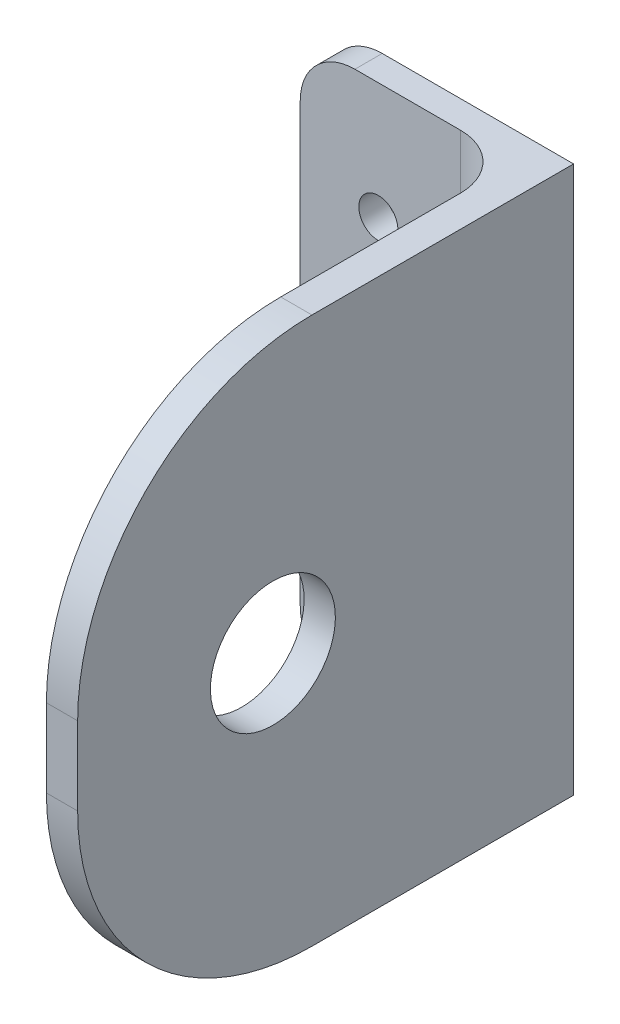
SolidWorks part; units mm, degrees
ref_plane "Plan de face" through (0, 0, 0) normal (0, 0, 1) x (1, 0, 0)
ref_plane "Plan de dessus" through (0, 0, 0) normal (0, 1, 0) x (1, 0, 0)
ref_plane "Plan de droite" through (0, 0, 0) normal (1, 0, 0) x (0, 0, -1)
sketch "Esquisse1" plane through (0, 0, 0) normal (0, 0, 1) x (1, 0, 0)
  line L0 (9.2703, 7.7568) -> (16.2703, 7.7568)
  line L1 (3.2703, 7.7568) -> (9.2703, 7.7568)
  line L2 (-3.7297, 0.7568) -> (-3.7297, -55.2432)
  line L3 (3.2703, -62.2432) -> (9.2703, -62.2432)
  line L4 (16.2703, 0.7568) -> (16.2703, -55.2432)
  line L5 (16.2703, 7.7568) -> (16.2703, 0.7568)
  line L6 (16.2703, -55.2432) -> (16.2703, -62.2432)
  line L7 (16.2703, -62.2432) -> (9.2703, -62.2432)
  arc A0 (-3.7297, -55.2432) -> (3.2703, -62.2432) centre (3.2703, -55.2432) ccw
  arc A3 (3.2703, 7.7568) -> (-3.7297, 0.7568) centre (3.2703, 0.7568) ccw
  point P8 (16.2703, -62.2432)
  point P11 (16.2703, 7.7568)
  point P14 (-3.7297, 7.7568)
  dimension "D3" = 7
  dimension "D1" = 20
  dimension "D2" = 70
extrude "Boss.-Extru.1" add sketch "Esquisse1" along normal blind 3.5
sketch "Esquisse2" plane through (0, 0, 3.5) normal (0, 0, 1) x (1, 0, 0)
  line L0 (16.2703, -62.2432) -> (16.2703, 7.7568) construction
  line L1 (16.2703, 7.7568) -> (3.2703, 7.7568) construction
  line L2 (3.2703, -62.2432) -> (16.2703, -62.2432) construction
  circle A0 centre (6.2703, -7.2432) radius 2.5
  circle A1 centre (6.2703, -47.2432) radius 2.5
  dimension "D1" = 10
  dimension "D2" = 10
  dimension "D3" = 5
  dimension "D4" = 5
  dimension "D5" = 15
  dimension "D6" = 15
extrude "Enlèv. mat.-Extru.1" cut sketch "Esquisse2" against normal blind 3.5
sketch "Esquisse3" plane through (0, 0, 3.5) normal (0, 0, 1) x (1, 0, 0)
  line L0 (23.7703, 7.7568) -> (23.7703, -62.2432) construction
  line L1 (16.2703, -62.2432) -> (16.2703, 7.7568) construction
  line L2 (16.2703, 7.7568) -> (3.2703, 7.7568) construction
  line L3 (3.2703, -62.2432) -> (16.2703, -62.2432) construction
  line L4 (23.7703, 7.7568) -> (27.7703, 7.7568)
  line L5 (23.7703, 7.7568) -> (23.7703, -62.2432)
  line L6 (23.7703, -62.2432) -> (27.7703, -62.2432)
  line L7 (27.7703, 7.7568) -> (27.7703, -62.2432)
  point P8 (0, 0)
  dimension "D1" = 7.5
  dimension "D2" = 4
  dimension "D3" = 0
  dimension "D4" = 0
extrude "Boss.-Extru.2" add sketch "Esquisse3" along normal blind 60 separate body
sketch "Esquisse4" plane through (27.7703, 0, 0) normal (1, 0, 0) x (0, 0, -1)
  line L0 (-63.5, 7.7568) -> (-3.5, 7.7568) construction
  line L1 (-3.5, -62.2432) -> (-3.5, 7.7568) construction
  circle A0 centre (-38.5, -27.2432) radius 8
  point P6 (-3.5, -27.2432)
  dimension "D1" = 16
  dimension "D2" = 35
  dimension "D3" = 35
extrude "Enlèv. mat.-Extru.2" cut sketch "Esquisse4" against normal blind 6
fillet "Congé1" radius 30 2 edges at (25.7703, -62.2432, 63.5) (25.7703, 7.7568, 63.5)
sketch "Esquisse5" plane through (16.2703, 0, 0) normal (1, 0, 0) x (0, 0, -1)
  line L1 (-3.5, 7.7568) -> (0, 7.7568)
  line L2 (-3.5, 7.7568) -> (-3.5, -62.2432)
  line L3 (-3.5, -62.2432) -> (0, -62.2432)
  line L4 (0, 7.7568) -> (0, -62.2432)
extrude "Boss.-Extru.4" add sketch "Esquisse5" along normal blind 11.5
fillet "Congé3" radius 7 1 edges at (23.7703, -27.2432, 3.5)
